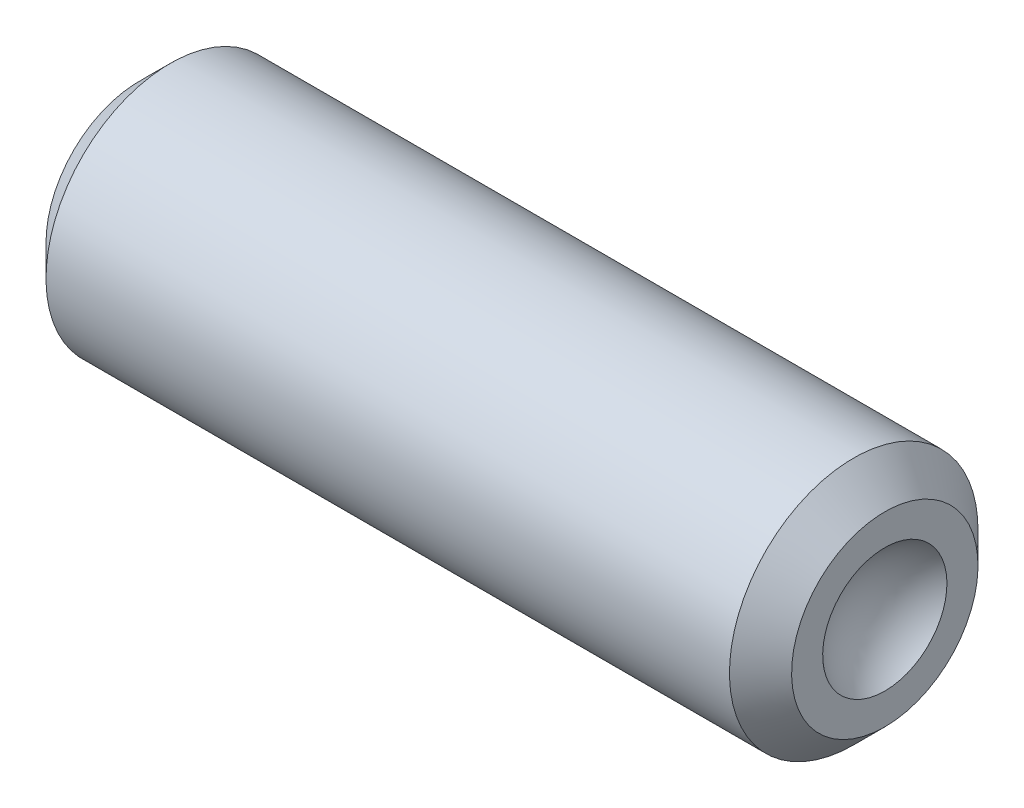
SolidWorks part; units mm, degrees
ref_plane "Front Plane" through (0, 0, 0) normal (0, 0, 1) x (1, 0, 0)
ref_plane "Top Plane" through (0, 0, 0) normal (0, 1, 0) x (1, 0, 0)
ref_plane "Right Plane" through (0, 0, 0) normal (1, 0, 0) x (0, 0, -1)
sketch "Sketch1" plane through (0, 0, 0) normal (0, 0, 1) x (1, 0, 0)
  line L0 (0, 0) -> (0, 1.5)
  line L1 (0, 1.5) -> (0.5, 2)
  line L2 (0.5, 2) -> (11.5, 2)
  line L3 (11.5, 2) -> (12, 1.5)
  line L4 (0, 0) -> (11.5, 0) construction
  line L5 (0.5, 2) -> (0.5, 1.5) construction
  line L6 (0.5, 1.5) -> (0.5, 1) construction
  line L7 (0.5, 1) -> (0.5, 0.5) construction
  line L8 (0.5, 0.5) -> (0.5, 0) construction
  line L9 (0.5, 1.5) -> (0, 1.5) construction
  line L10 (11.5, 2) -> (11.5, 0) construction
  line L11 (12, 1.5) -> (12, 1)
  line L12 (0, 0) -> (11.5, 0)
  arc A0 (11.5, 0) -> (12, 1) centre (12.75, 0) cw
  dimension "D1" = 45
  dimension "D2" = 4
  dimension "D3" = 12
  dimension "D4" = 2
revolve "Revolve1" add sketch "Sketch1" angle 360 about L12
sketch "Sketch2" plane through (0, 0, 0) normal (-1, 0, 0) x (0, 0, 1)
  line L1 (0, 1.1547) -> (-1, 0.5774)
  line L2 (-1, 0.5774) -> (-1, -0.5774)
  line L3 (-1, -0.5774) -> (0, -1.1547)
  line L4 (0, -1.1547) -> (1, -0.5774)
  line L5 (1, -0.5774) -> (1, 0.5774)
  line L6 (1, 0.5774) -> (0, 1.1547)
  circle A0 centre (0, 0) radius 1 construction
  dimension "D1" = 2
extrude "Cut-Extrude1" cut sketch "Sketch2" against normal offset from surface (10 mm away) 2 up to face at (12, -1.5, 0)
